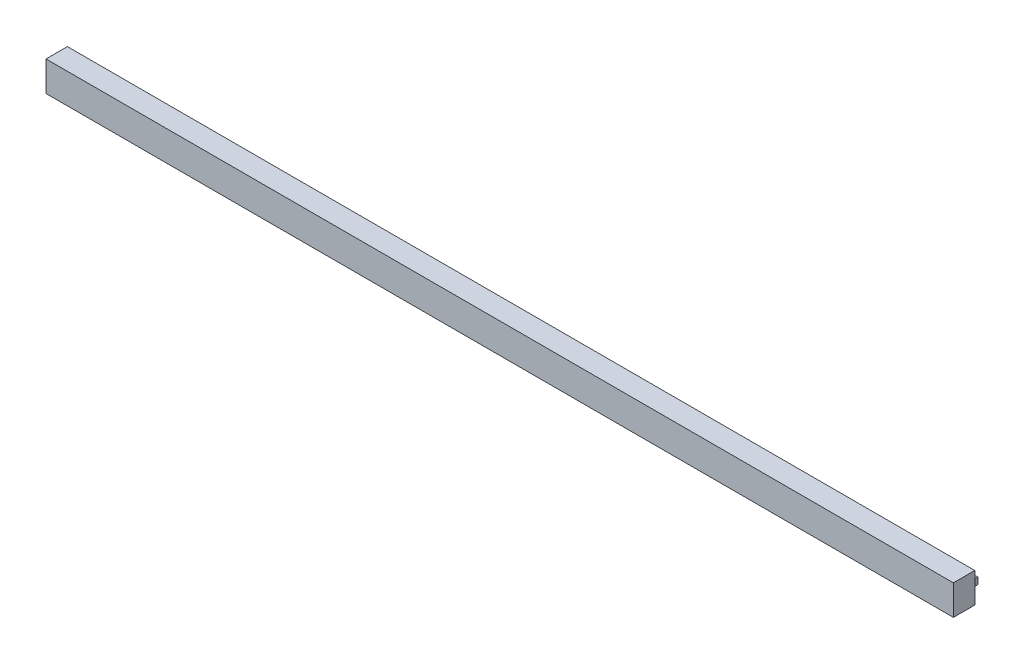
SolidWorks part; units mm, degrees
ref_plane "Front Plane" through (0, 0, 0) normal (0, 0, 1) x (1, 0, 0)
ref_plane "Top Plane" through (0, 0, 0) normal (0, 1, 0) x (1, 0, 0)
ref_plane "Right Plane" through (0, 0, 0) normal (1, 0, 0) x (0, 0, -1)
sketch "Sketch1" plane through (0, 0, 0) normal (0, 0, 1) x (1, 0, 0)
  line L1 (0, 0) -> (212, 0)
  line L2 (0, 0) -> (0, 7)
  line L3 (0, 7) -> (212, 7)
  line L4 (212, 0) -> (212, 7)
  dimension "D1" = 212
  dimension "D2" = 7
extrude "Boss-Extrude1" add sketch "Sketch1" along normal blind 5
sketch "Sketch2" plane through (0, 0, 0) normal (0, 0, -1) x (-1, 0, 0)
  line L0 (-208.5, 1.7685) -> (-210.5, 1.7685) construction
  line L1 (-210.5, 1.7685) -> (-210.5, 3.7685) construction
  line L2 (-210.5, 3.7685) -> (-208.5, 3.7685) construction
  line L3 (-208.5, 3.7685) -> (-208.5, 1.7685) construction
  line L4 (-1.5, 1.7685) -> (-3.5, 1.7685) construction
  line L5 (-3.5, 1.7685) -> (-3.5, 3.7685) construction
  line L6 (-3.5, 3.7685) -> (-1.5, 3.7685) construction
  line L7 (-1.5, 3.7685) -> (-1.5, 1.7685) construction
  line L8 (-208.5, 1.7685) -> (-210.5, 1.7685)
  line L9 (-210.5, 1.7685) -> (-210.5, 3.7685)
  line L10 (-210.5, 3.7685) -> (-208.5, 3.7685)
  line L11 (-208.5, 3.7685) -> (-208.5, 1.7685)
  line L12 (-1.5, 1.7685) -> (-3.5, 1.7685)
  line L13 (-3.5, 1.7685) -> (-3.5, 3.7685)
  line L14 (-3.5, 3.7685) -> (-1.5, 3.7685)
  line L15 (-1.5, 3.7685) -> (-1.5, 1.7685)
  line L16 (-3.25, 2.0185) -> (-3.25, 3.5185)
  line L17 (-3.25, 3.5185) -> (-1.75, 3.5185)
  line L18 (-1.75, 3.5185) -> (-1.75, 2.0185)
  line L19 (-1.75, 2.0185) -> (-3.25, 2.0185)
  line L20 (-210.25, 2.0185) -> (-210.25, 3.5185)
  line L21 (-210.25, 3.5185) -> (-208.75, 3.5185)
  line L22 (-208.75, 3.5185) -> (-208.75, 2.0185)
  line L23 (-208.75, 2.0185) -> (-210.25, 2.0185)
  dimension "D1" = 0.25
extrude "Boss-Extrude2" add sketch "Sketch2" along normal blind 2.5 contours L22 L23 L20 L21 | L18 L19 L16 L17
